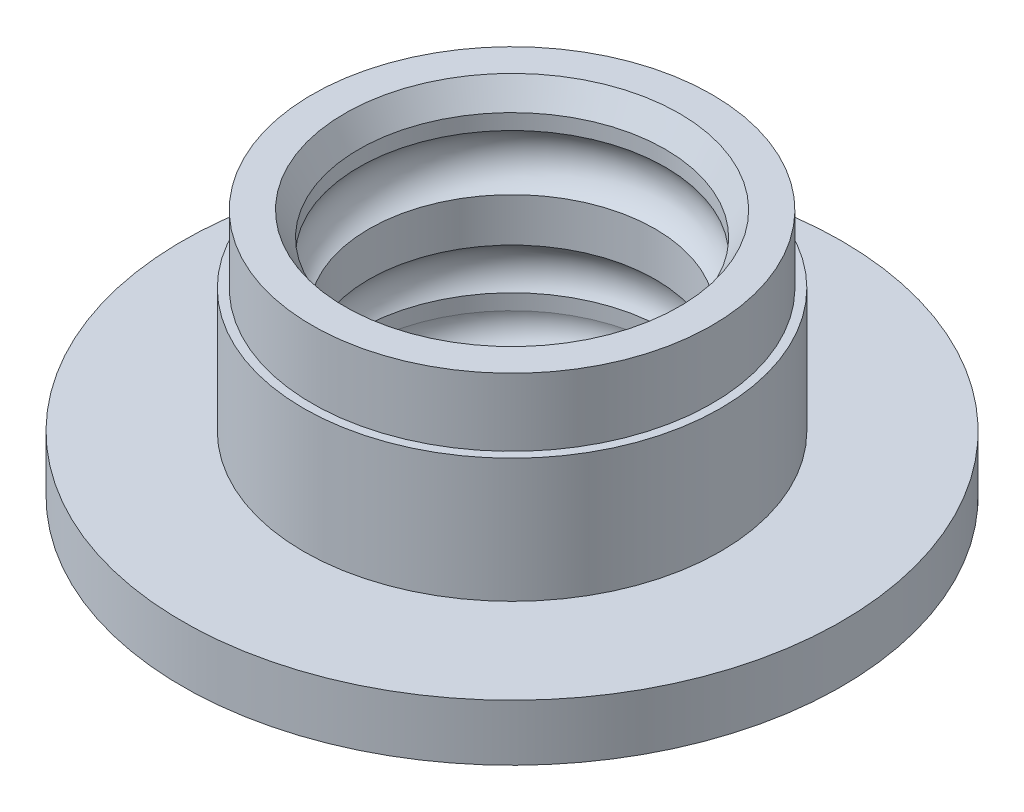
SolidWorks part; units mm, degrees
ref_plane "Plano frontal" through (0, 0, 0) normal (0, 0, 1) x (1, 0, 0)
ref_plane "Plano superior" through (0, 0, 0) normal (0, 1, 0) x (1, 0, 0)
ref_plane "Plano direito" through (0, 0, 0) normal (1, 0, 0) x (0, 0, -1)
sketch "Esboço1" plane through (0, 0, 0) normal (0, 0, 1) x (1, 0, 0)
  line L0 (0, -64.8431) -> (0, 71.0534) construction
  line L1 (29.7, 13.7406) -> (35.5, 13.7406)
  line L2 (35.5, 13.7406) -> (35.5, 1.7406)
  line L3 (35.5, 1.7406) -> (37, 1.7406)
  line L4 (37, -20.2594) -> (58.5, -20.2594)
  line L5 (58.5, -20.2594) -> (58.5, -30.2594)
  line L6 (58.5, -30.2594) -> (29.5, -30.2594)
  line L7 (29.5, -30.2594) -> (29.5, -35.2594)
  line L8 (29.5, -35.2594) -> (29, -35.2594)
  line L9 (29, -35.2594) -> (29, -47.2594)
  line L10 (29, -47.2594) -> (26, -47.2594)
  line L11 (26, -47.2594) -> (26, -36.2594)
  line L12 (26, -36.2594) -> (25.8, -36.2594)
  line L13 (25.8, -36.2594) -> (25.8, -25.4594)
  line L14 (27.1891, -20.9594) -> (27.1891, -18.2094)
  line L15 (25.4, -9.6094) -> (25.4, -1.8594)
  line L16 (25.4, -5.7344) -> (16.0486, -5.7344) construction
  line L17 (27.1891, 9.4906) -> (27.1891, 6.7406)
  line L18 (27.1891, 9.4906) -> (29.7, 13.7406)
  line L19 (37, 1.7406) -> (37, -20.2594)
  arc A0 (25.8, -25.4594) -> (27.1891, -20.9594) centre (22.28, -21.9084) ccw
  arc A1 (27.1891, -18.2094) -> (25.4, -9.6094) centre (22.6612, -14.6653) ccw
  arc A2 (27.1891, 6.7406) -> (25.4, -1.8594) centre (22.6612, 3.1964) cw
  dimension "D10" = 5
  dimension "D12" = 5.75
  dimension "D14" = 7
  dimension "D1" = 25.8
  dimension "D2" = 26
  dimension "D3" = 11
  dimension "D4" = 5
  dimension "D5" = 17
  dimension "D6" = 10
  dimension "D7" = 29
  dimension "D8" = 29.5
  dimension "D9" = 58.5
  dimension "D11" = 2.75
  dimension "D13" = 7.75
  dimension "D15" = 29.7
  dimension "D16" = 25.4
  dimension "D17" = 8.6
  dimension "D18" = 35.5
  dimension "D19" = 37
  dimension "D20" = 44
  dimension "D21" = 21.8
  dimension "D22" = 12
revolve "Revolução1" add sketch "Esboço1" angle 360 about L0
